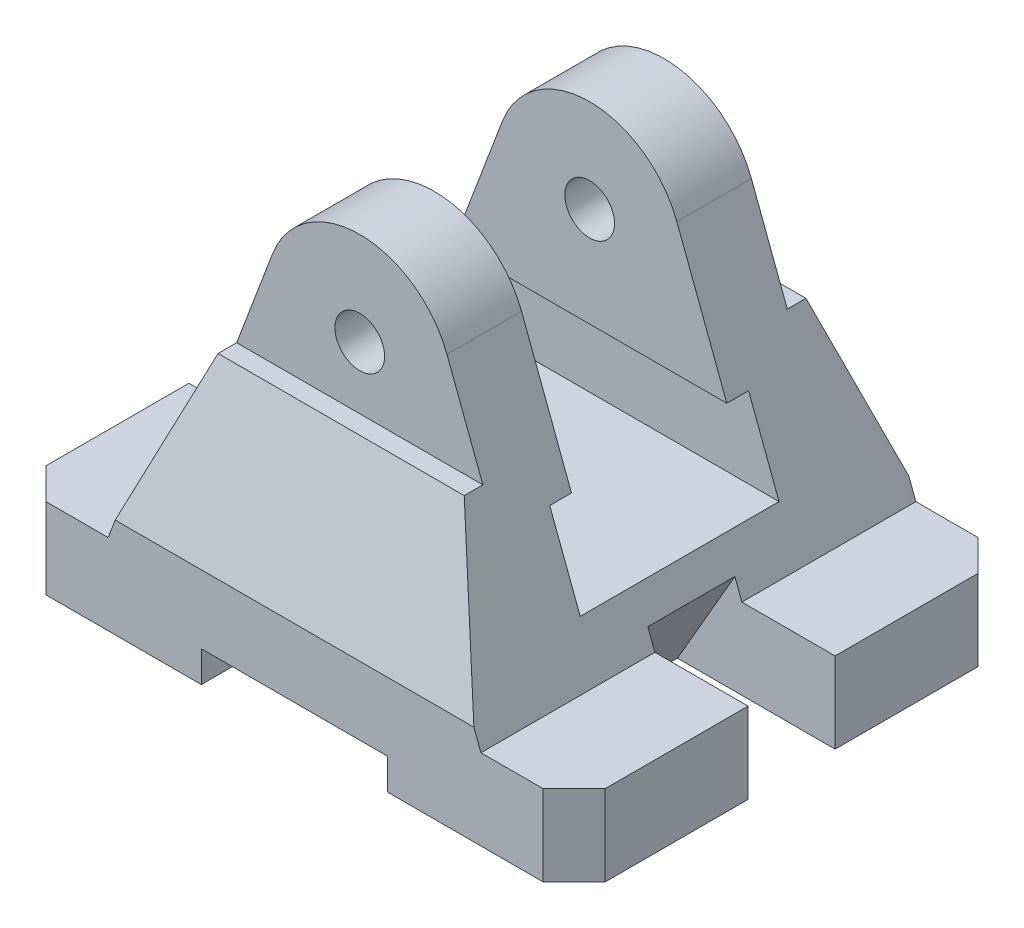
SolidWorks part; units mm, degrees
ref_plane "Front Plane" through (0, 0, 0) normal (0, 0, 1) x (1, 0, 0)
ref_plane "Top Plane" through (0, 0, 0) normal (0, 1, 0) x (1, 0, 0)
ref_plane "Right Plane" through (0, 0, 0) normal (1, 0, 0) x (0, 0, -1)
sketch "Sketch1" plane through (0, 0, 0) normal (1, 0, 0) x (0, 0, -1)
  line L1 (35, -6.5) -> (-35, -6.5)
  line L2 (35, -6.5) -> (35, 6.5)
  line L3 (35, 6.5) -> (-35, 6.5)
  line L4 (-35, -6.5) -> (-35, 6.5)
  line L5 (35, -6.5) -> (-35, 6.5) construction
  line L6 (35, 6.5) -> (-35, -6.5) construction
  point P0 (0, 0)
  point P6 (0, 0)
  dimension "D1" = 70
  dimension "D2" = 13
extrude "Boss-Extrude1" add sketch "Sketch1" along normal mid plane 90
chamfer "Chamfer1" distance 5 angle 45 4 edges at (-45, 0, 35) (-45, 0, -35) (45, 0, -35) (45, 0, 35)
sketch "Sketch3" plane through (0, 0, 0) normal (0, 0, 1) x (1, 0, 0)
  line L0 (40, -6.5) -> (-40, -6.5) construction
  line L1 (-15, -6.5) -> (15, -6.5)
  line L2 (-15, -6.5) -> (-15, -1.5)
  line L3 (-15, -1.5) -> (15, -1.5)
  line L4 (15, -6.5) -> (15, -1.5)
  line L5 (0, 0) -> (0, 50000) construction
  point P6 (0, 0)
  dimension "D1" = 30
  dimension "D2" = 5
extrude "Cut-Extrude1" cut sketch "Sketch3" against normal through all and the other way through all
sketch "Sketch4" plane through (0, 0, 0) normal (0, 0, 1) x (1, 0, 0)
  line L0 (0, 0) -> (0, 50000) construction
  line L1 (-30, 6.5) -> (-14.0334, 48.7974)
  line L2 (40, 6.5) -> (-40, 6.5) construction
  line L3 (14.0334, 48.7974) -> (30, 6.5)
  line L4 (-30, 6.5) -> (30, 6.5)
  arc A0 (-14.0334, 48.7974) -> (14.0334, 48.7974) centre (0, 43.5) cw
  point P9 (0, 0)
  point P11 (12.939, 35.591)
  dimension "D1" = 15
  dimension "D2" = 60
  dimension "D3" = 50
extrude "Boss-Extrude2" add sketch "Sketch4" along normal through all and the other way through all
sketch "Sketch13" plane through (0, 0, 0) normal (1, 0, 0) x (0, 0, -1)
  line L0 (-35, 9.5) -> (-27.5, 33.5)
  line L1 (-35, 6.5) -> (-35, 48.7974) construction
  line L2 (-27.5, 33.5) -> (-24.5, 33.5)
  line L3 (-24.5, 33.5) -> (-24.5, 58.5)
  line L4 (35, 58.5) -> (-35, 58.5) construction
  line L5 (-24.5, 58.5) -> (-12.5, 58.5)
  line L6 (-12.5, 58.5) -> (-12.5, 27.5)
  line L7 (-12.5, 27.5) -> (-16, 27.5)
  line L8 (-16, 27.5) -> (-16, 14.5)
  line L9 (-16, 14.5) -> (16, 14.5)
  line L10 (-30, -6.5) -> (30, -6.5) construction
  line L11 (0, 0) -> (0, 50000) construction
  line L12 (16, 27.5) -> (16, 14.5)
  line L13 (12.5, 27.5) -> (16, 27.5)
  line L14 (12.5, 58.5) -> (12.5, 27.5)
  line L15 (24.5, 58.5) -> (12.5, 58.5)
  line L16 (24.5, 33.5) -> (24.5, 58.5)
  line L17 (27.5, 33.5) -> (24.5, 33.5)
  line L18 (35, 9.5) -> (27.5, 33.5)
  point P19 (0, 14.5)
  dimension "D1" = 16
  dimension "D2" = 3
  dimension "D3" = 13
  dimension "D4" = 25
  dimension "D5" = 49
  dimension "D6" = 21
  dimension "D7" = 32
  dimension "D8" = 40
extrude "Cut-Extrude11" cut sketch "Sketch13" against normal through all and the other way through all flip side to cut
sketch "Sketch14" plane through (0, 0, 0) normal (0, 0, 1) x (1, 0, 0)
  line L0 (28.8676, 9.5) -> (19.6299, -6.5)
  line L1 (40, -6.5) -> (15, -6.5) construction
  line L2 (19.6299, -6.5) -> (45, -6.5)
  line L3 (45, -6.5) -> (45, 6.5)
  line L4 (45, 6.5) -> (30, 6.5)
  line L5 (30, 6.5) -> (28.8676, 9.5)
  dimension "D1" = 60
extrude "Cut-Extrude12" cut sketch "Sketch14" against normal mid plane 14
mirror "Mirror1" about plane through (0, 0, 0) normal (1, 0, 0) of "Cut-Extrude12"
hole_wizard "Ø8.0 (8) Diameter Hole2" positions "Sketch15" profile "Sketch16" hole size "Ø8.0" standard "ISO" end condition through all
sketch "Sketch15" plane through (0, 0, 24.5) normal (0, 0, 1) x (1, 0, 0)
  line L0 (0, 0) -> (0, 50000) construction
  line L1 (40, -6.5) -> (15, -6.5) construction
  point P0 (0, 43.5)
  point P7 (0, 0)
  dimension "D1" = 50
sketch "Sketch16" plane through (0, 43.5, 24.5) normal (1, 0, 0) x (0, -1, 0)
  line L0 (0, 0) -> (0, 59.5)
  line L1 (0, 59.5) -> (4, 59.5)
  line L2 (4, 59.5) -> (4, 0)
  line L5 (4, 0) -> (0, 0)
  line L11 (0, -6.35) -> (0, 107.95) construction
  dimension "Thru Hole Dia." = 8
  dimension "Thru Hole Depth" = 59.5
hole_wizard "M12 Tapped Hole1" positions "Sketch17" profile "Sketch18" tap size "M12" standard "ISO" end condition through all
sketch "Sketch17" plane through (0, 14.5, 0) normal (0, 1, 0) x (1, 0, 0)
  point P0 (0, 0)
sketch "Sketch18" plane through (0, 14.5, 0) normal (1, 0, 0) x (0, 0, 1)
  line L0 (0, 0) -> (0, 21)
  line L1 (0, 21) -> (5.1, 21)
  line L2 (5.1, 21) -> (5.1, 0)
  line L5 (5.1, 0) -> (0, 0)
  line L11 (0, -6.35) -> (0, 107.95) construction
  dimension "Thru Tap Drill Dia." = 10.2
  dimension "Thru Tap Drill Depth" = 21
cosmetic thread "Hole Thread1" parameters "D2"=12
